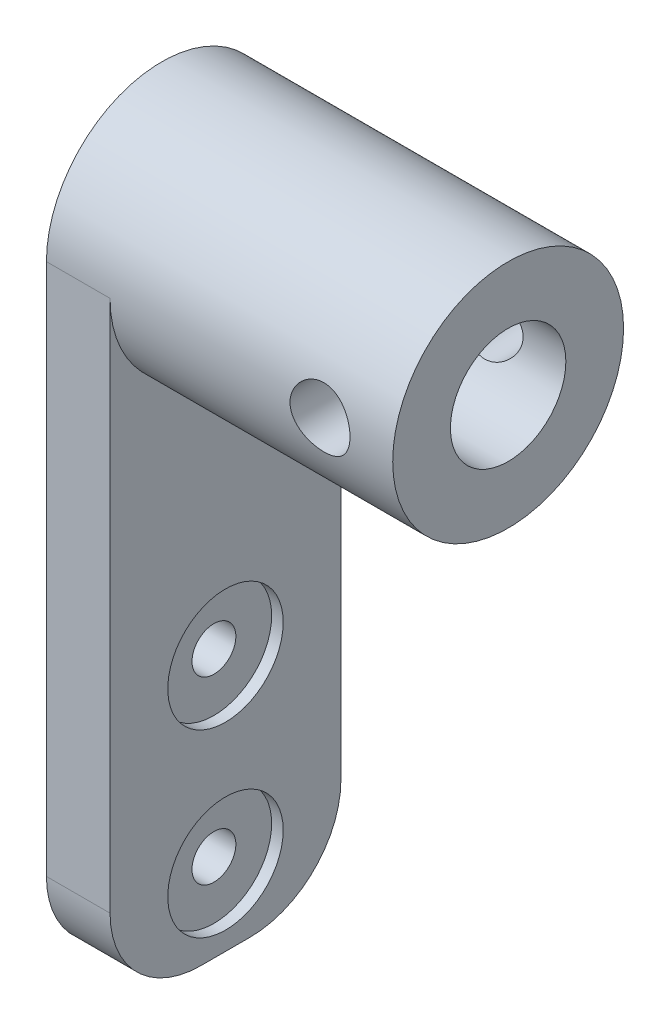
SolidWorks part; units mm, degrees
material "ABS"
ref_plane "Front Plane" through (0, 0, 0) normal (1, 0, 0) x (0, 1, 0)
ref_plane "Top Plane" through (0, 0, 0) normal (0, 0, 1) x (0, 1, 0)
ref_plane "Right Plane" through (0, 0, 0) normal (0, 1, 0) x (-1, 0, 0)
sketch "Sketch1" plane through (0, 0, 0) normal (1, 0, 0) x (0, 1, 0)
  circle A0 centre (0, 0) radius 3.175
  circle A1 centre (0, 0) radius 3
  circle A2 centre (0, 0) radius 6.35
  dimension "D1" = 6
  dimension "D2" = 6.35
  dimension "D3" = 12.7
extrude "Boss-Extrude1" add sketch "Sketch1" along normal blind 19.05 contours A2 A0
ref_plane "Plane1" through (0, 0, 6.35) normal (0, 0, 1) x (0, 1, 0)
sketch "Sketch7" plane through (0, 0, 6.35) normal (0, 0, 1) x (0, 1, 0)
  line L2 (-6.35, -19.05) -> (6.35, -19.05) construction
  circle A0 centre (0, -15.05) radius 1.0922
  point P0 (0, -15.05)
  dimension "D2" = 2.1844
  dimension "D1" = 4
hole_wizard "M4x0.7 Tapped Hole1" positions "Sketch7" profile "Sketch9" tap size "M4x0.7" standard "ANSI Metric" end condition through all
sketch "Sketch9" plane through (15.05, 0, 6.35) normal (1, 0, 0) x (0, -1, 0)
  line L0 (0, 0) -> (0, 12.7)
  line L1 (0, 12.7) -> (1.65, 12.7)
  line L2 (1.65, 12.7) -> (1.65, 0)
  line L5 (1.65, 0) -> (0, 0)
  line L11 (0, -6.35) -> (0, 107.95) construction
  dimension "Thru Tap Drill Dia." = 3.3
  dimension "Thru Tap Drill Depth" = 12.7
cosmetic thread "Hole Thread10" parameters "D2"=4
sketch "Sketch10" plane through (0, 0, 0) normal (-1, 0, 0) x (0, -1, 0)
  line L0 (0, 6.35) -> (34.29, 6.35)
  line L1 (14.575, 6.35) -> (-14.575, 6.35) construction
  line L2 (34.29, 6.35) -> (34.29, -6.35)
  line L3 (34.29, -6.35) -> (0, -6.35)
  circle A0 centre (0, 0) radius 6.35 construction
  arc A1 (-1.65, -6.1319) -> (1.65, -6.1319) centre (0, 0) ccw construction
  arc A2 (0, 6.35) -> (0, -6.35) centre (0, 0) cw
  dimension "D1" = 34.29
extrude "Boss-Extrude3" add sketch "Sketch10" against normal blind 3.5 contours L0 A2 L3 L2
fillet "Fillet2" radius 5 2 edges at (1.75, -34.29, 6.35) (1.75, -34.29, -6.35)
sketch "Sketch11" plane through (0, 0, 0) normal (-1, 0, 0) x (0, -1, 0)
  line L0 (34.29, 0) -> (0, 0) construction
  line L1 (34.29, 1.35) -> (34.29, -1.35) construction
  circle A0 centre (30.099, 0) radius 1.2065
  circle A1 centre (20.193, 0) radius 1.2065
  dimension "D3" = 2.413
  dimension "D1" = 4.191
  dimension "D2" = 9.906
extrude "Cut-Extrude1" cut sketch "Sketch11" against normal through all
sketch "Sketch12" plane through (3.5, 0, 0) normal (1, 0, 0) x (0, 1, 0)
  circle A0 centre (-20.193, 0) radius 3.175
  circle A1 centre (-30.099, 0) radius 3.175
  dimension "D1" = 6.35
extrude "Cut-Extrude2" cut sketch "Sketch12" against normal blind 0.635
